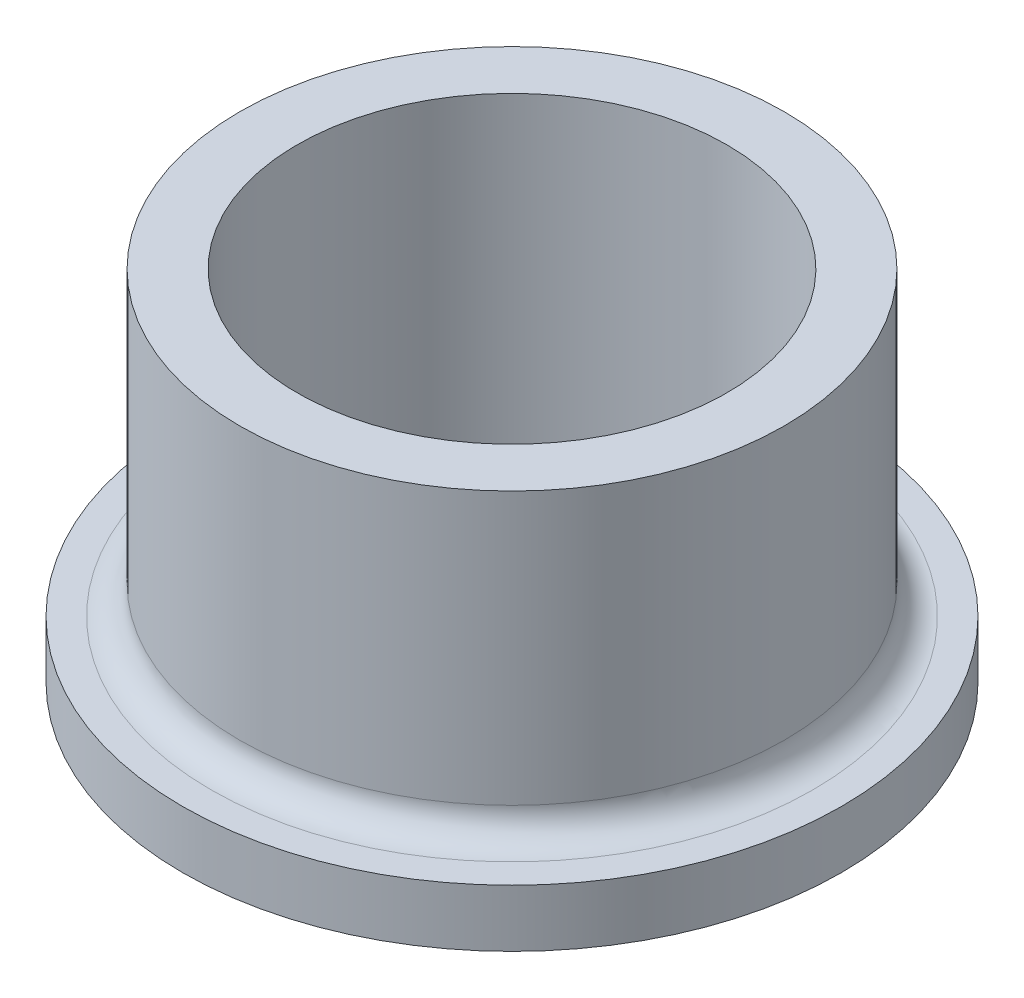
SolidWorks part; units mm, degrees
ref_plane "Front Plane" through (0, 0, 0) normal (0, 0, 1) x (1, 0, 0)
ref_plane "Top Plane" through (0, 0, 0) normal (0, 1, 0) x (1, 0, 0)
ref_plane "Right Plane" through (0, 0, 0) normal (1, 0, 0) x (0, 0, -1)
sketch "Sketch1" plane through (0, 0, 0) normal (0, 0, 1) x (1, 0, 0)
  line L0 (0, 0) -> (0, 25) construction
  line L1 (15, 25) -> (15, 2)
  line L2 (17, 0) -> (23, 0)
  line L3 (23, 0) -> (23, 4)
  line L4 (23, 4) -> (21, 4)
  line L5 (19, 6) -> (19, 25)
  line L6 (19, 25) -> (15, 25)
  arc A0 (21, 4) -> (19, 6) centre (21, 6) cw
  arc A1 (15, 2) -> (17, 0) centre (17, 2) ccw
  point P15 (15, 0)
  dimension "D6" = 2
  dimension "D7" = 2
  dimension "D1" = 25
  dimension "D2" = 15
  dimension "D3" = 8
  dimension "D4" = 4
  dimension "D5" = 4
revolve "Revolve1" add sketch "Sketch1" angle 360 about L0
